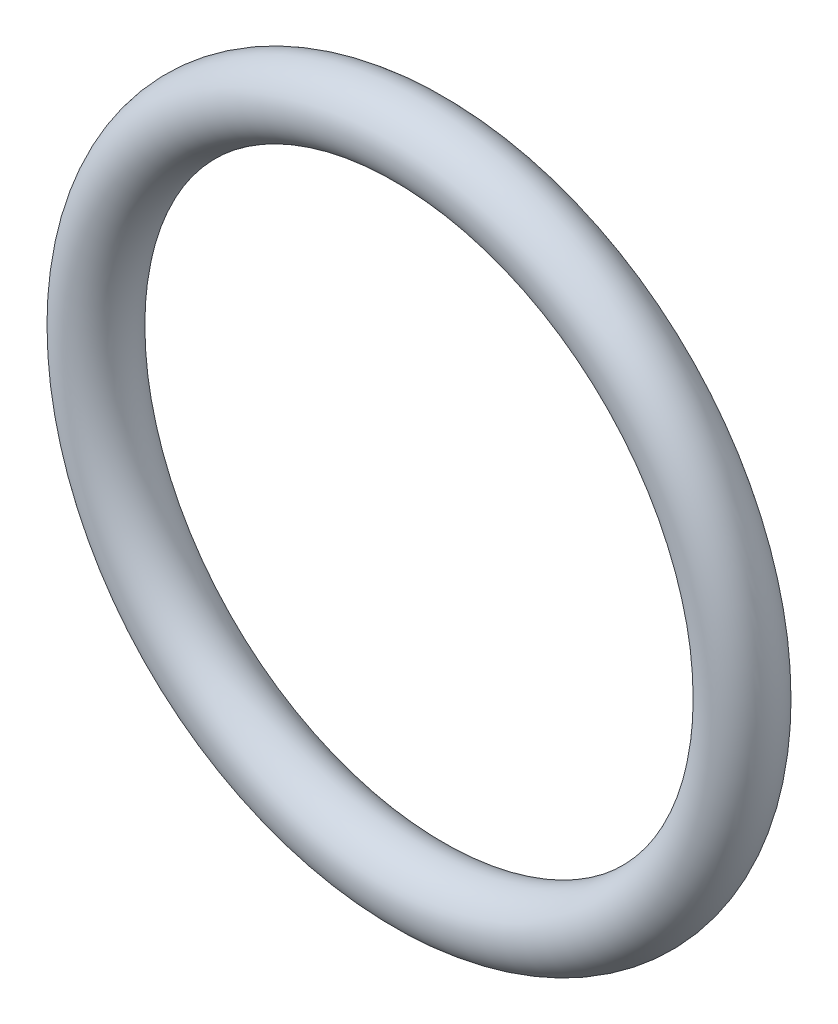
SolidWorks part; units mm, degrees
material "Rubber"
ref_plane "Front" through (0, 0, 0) normal (0, 0, 1) x (1, 0, 0)
ref_plane "Top" through (0, 0, 0) normal (0, 1, 0) x (1, 0, 0)
ref_plane "Right" through (0, 0, 0) normal (1, 0, 0) x (0, 0, -1)
sketch "Sketch1" plane through (0, 0, 0) normal (1, 0, 0) x (0, -1, 0)
  line L0 (0, -1.5) -> (0, 1.5) construction
  line L2 (-17.05, 0) -> (17.05, 0) construction
  line L3 (-12.5, 0) -> (12.5, 0) construction
  circle A0 centre (14, 0) radius 1.5
  point P9 (12.5, 0)
  point P10 (15.5, 0)
  point P13 (14, 1.5)
  point P14 (14, -1.5)
  dimension "Width" = 3
  dimension "ID" = 25
revolve "Revolve1" add sketch "Sketch1" angle 360 about L0
